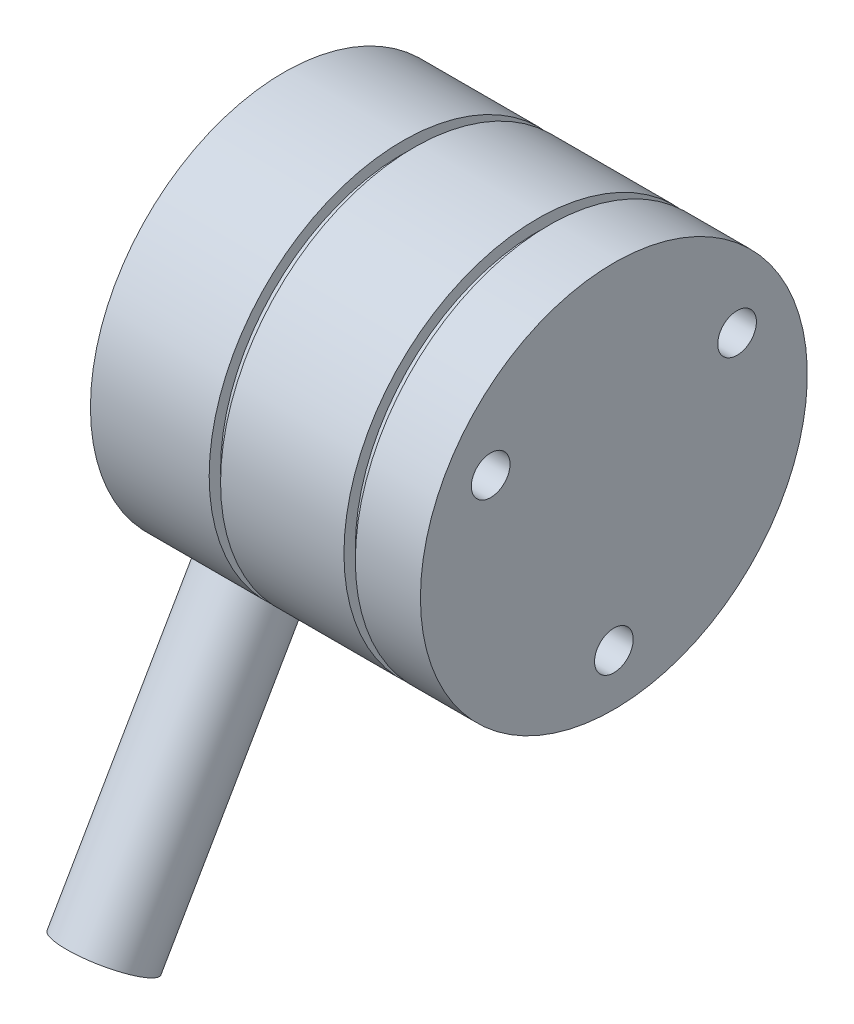
SolidWorks part; units mm, degrees
ref_plane "Front Plane" through (0, 0, 0) normal (0, 0, 1) x (1, 0, 0)
ref_plane "Top Plane" through (0, 0, 0) normal (0, 1, 0) x (1, 0, 0)
ref_plane "Right Plane" through (0, 0, 0) normal (1, 0, 0) x (0, 0, -1)
sketch "Sketch1" plane through (0, 0, 0) normal (0, 0, 1) x (1, 0, 0)
  line L0 (0, 0) -> (14.5, 0) construction
  line L1 (0, 0) -> (0, 8.5)
  line L2 (0, 8.5) -> (5.2178, 8.5)
  line L3 (5.2178, 8.5) -> (5.2178, 8)
  line L4 (5.2178, 8) -> (5.7178, 8)
  line L5 (5.7178, 8) -> (5.7178, 8.5)
  line L6 (5.7178, 8.5) -> (11.1393, 8.5)
  line L7 (11.1393, 8.5) -> (11.1393, 8)
  line L8 (11.1393, 8) -> (11.6393, 8)
  line L9 (11.6393, 8) -> (11.6393, 8.5)
  line L10 (11.6393, 8.5) -> (14.5, 8.5)
  line L11 (14.5, 8.5) -> (14.5, 0)
  line L12 (0, 0) -> (14.5, 0)
  dimension "D1" = 14.5
  dimension "D2" = 0.5
  dimension "D3" = 17
revolve "Revolve1" add sketch "Sketch1" angle 360 about L0
sketch "Sketch2" plane through (0, 0, 0) normal (-1, 0, 0) x (0, 0, 1)
  line L0 (6.2262, -0.5447) -> (0, 0) construction
  line L1 (0, 0) -> (11.1506, 0) construction
  circle A0 centre (0, 0) radius 6.25 construction
  circle A1 centre (-2.6414, 5.6644) radius 0.85
  circle A2 centre (6.2262, -0.5447) radius 0.85
  circle A3 centre (-3.5849, -5.1197) radius 0.85
  point P11 (0, 0)
  dimension "D1" = 12.5
  dimension "D2" = 1.7
  dimension "D4" = 5
  dimension "D3" = 3
extrude "Cut-Extrude1" cut sketch "Sketch2" against normal blind 2.54
ref_plane "Plane1" through (0, -7.3612, 4.25) normal (0, -0.866, 0.5) x (1, 0, 0)
sketch "Sketch3" plane through (0, -7.3612, 4.25) normal (0, -0.866, 0.5) x (1, 0, 0)
  circle A0 centre (2.6945, 0) radius 1.9
  dimension "D1" = 3.8
extrude "Boss-Extrude1" add sketch "Sketch3" along normal blind 12.7 and the other way blind 2.54
sketch "Sketch4" plane through (14.5, 0, 0) normal (1, 0, 0) x (0, 0, -1)
  circle A0 centre (0, 0) radius 6.25 construction
  circle A1 centre (0, -6.25) radius 0.85
  circle A2 centre (-5.4127, 3.125) radius 0.85
  circle A3 centre (5.4127, 3.125) radius 0.85
  point P11 (0, 0)
  dimension "D1" = 12.5
  dimension "D2" = 1.7
  dimension "D3" = 3
extrude "Cut-Extrude2" cut sketch "Sketch4" against normal blind 2.794
